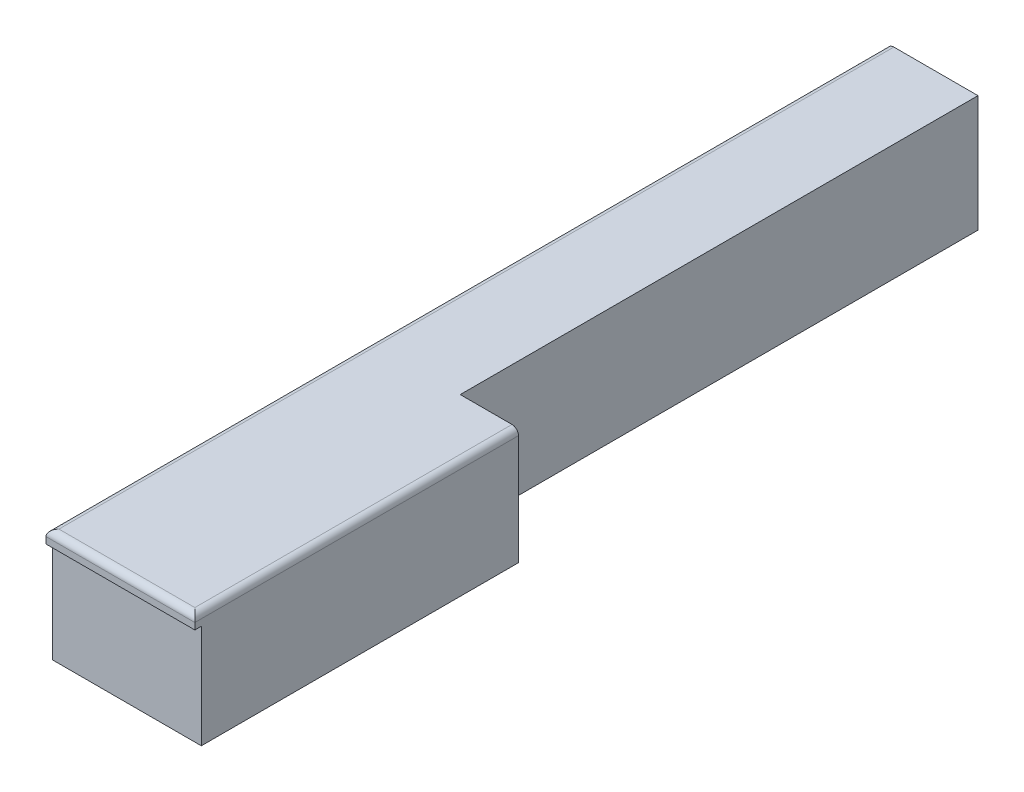
SolidWorks part; units mm, degrees
material "Pino"
ref_plane "Alzado" through (0, 0, 0) normal (0, 0, 1) x (1, 0, 0)
ref_plane "Planta" through (0, 0, 0) normal (0, 1, 0) x (1, 0, 0)
ref_plane "Vista lateral" through (0, 0, 0) normal (1, 0, 0) x (0, 0, -1)
sketch "Croquis2" plane through (0, 0, 0) normal (0, 1, 0) x (1, 0, 0)
  line L1 (0, 0) -> (23, 0)
  line L2 (0, 0) -> (0, 130)
  line L3 (0, 130) -> (23, 130)
  line L4 (23, 0) -> (23, 130)
  line L5 (23, 130) -> (14, 130)
  line L6 (23, 130) -> (23, 50)
  line L7 (23, 50) -> (14, 50)
  line L8 (14, 130) -> (14, 50)
  dimension "D1" = 23
  dimension "D2" = 130
  dimension "D3" = 50
  dimension "D4" = 14
extrude "Saliente-Extruir1" add sketch "Croquis2" along normal blind 18
sketch "Croquis3" plane through (0, 0, 0) normal (0, 0, 1) x (1, 0, 0)
  line L0 (23, 18) -> (23, 0) construction
  line L1 (0, 0) -> (23, 0)
  line L2 (0, 0) -> (0, 16)
  line L3 (0, 16) -> (23, 16)
  line L4 (23, 0) -> (23, 16)
extrude "Cortar-Extruir1" cut sketch "Croquis3" against normal blind 1
fillet "Redondeo1" radius 1 3 edges at (11.5, 18, 0) (0, 18, -65) (23, 18, -25)
